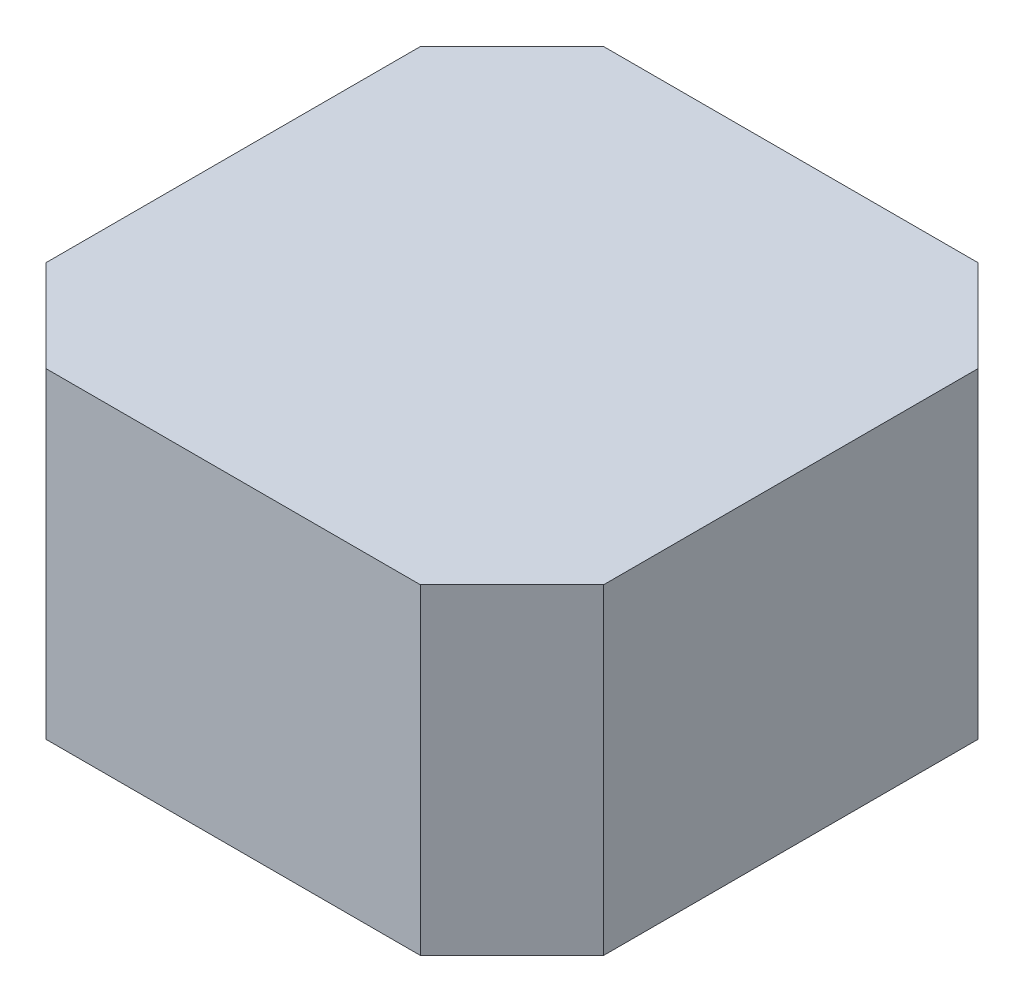
SolidWorks part; units mm, degrees
material "6061-T6 (SS)"
ref_plane "Front Plane" through (0, 0, 0) normal (0, 0, 1) x (1, 0, 0)
ref_plane "Top Plane" through (0, 0, 0) normal (0, 1, 0) x (1, 0, 0)
ref_plane "Right Plane" through (0, 0, 0) normal (1, 0, 0) x (0, 0, -1)
sketch "Sketch2" plane through (0, 0, 0) normal (0, 1, 0) x (1, 0, 0)
  line L1 (0, 0) -> (6.08, 0)
  line L2 (0, 0) -> (0, 6.08)
  line L3 (0, 6.08) -> (6.08, 6.08)
  line L4 (6.08, 0) -> (6.08, 6.08)
  dimension "D1" = 6.08
  dimension "D2" = 6.08
extrude "Boss-Extrude1" add sketch "Sketch2" along normal blind 3.5
chamfer "Chamfer1" distance 1 angle 45 4 edges at (6.08, 1.75, -6.08) (0, 1.75, -6.08) (0, 1.75, 0) (6.08, 1.75, 0)
